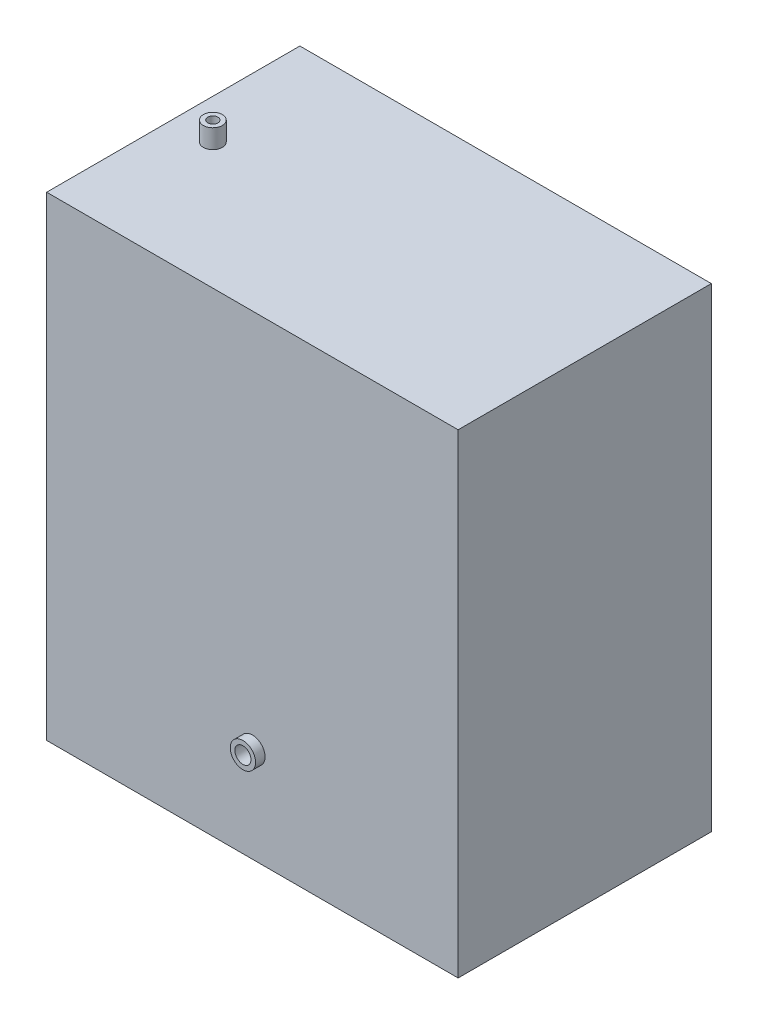
SolidWorks part; units mm, degrees
ref_plane "Front Plane" through (0, 0, 0) normal (0, 0, 1) x (1, 0, 0)
ref_plane "Top Plane" through (0, 0, 0) normal (0, 1, 0) x (1, 0, 0)
ref_plane "Right Plane" through (0, 0, 0) normal (1, 0, 0) x (0, 0, -1)
other "Configuration Table"
sketch "Sketch1" plane through (0, 0, 0) normal (0, 1, 0) x (1, 0, 0)
  line L1 (-130, -80) -> (130, -80)
  line L2 (-130, -80) -> (-130, 80)
  line L3 (-130, 80) -> (130, 80)
  line L4 (130, -80) -> (130, 80)
  line L5 (-130, -80) -> (130, 80) construction
  line L6 (-130, 80) -> (130, -80) construction
  point P6 (0, 0)
  dimension "D1" = 260
  dimension "D2" = 160
extrude "Tank_Body" add sketch "Sketch1" along normal blind 300
sketch "Sketch2" plane through (0, 0, 0) normal (0, 1, 0) x (1, 0, 0)
  line L0 (-127, -77) -> (127, -77)
  line L1 (127, -77) -> (127, 77)
  line L2 (127, 77) -> (-127, 77)
  line L3 (-127, 77) -> (-127, -77)
extrude "Inside" cut sketch "Sketch2" against normal blind 294 from offset 297
sketch "Sketch3" plane through (0, 0, 0) normal (0, 1, 0) x (1, 0, 0)
  circle A0 centre (-105, 0) radius 6
  dimension "D1" = 12
extrude "Inlet_Port" add sketch "Sketch3" along normal blind 12 from offset 300
sketch "Sketch4" plane through (0, 0, 0) normal (0, 1, 0) x (1, 0, 0)
  circle A0 centre (-105, 0) radius 3.2
  dimension "D1" = 6.4
extrude "Inlet_Socket" cut sketch "Sketch4" against normal blind 10 from offset 312
sketch "Sketch5" plane through (0, 0, 0) normal (0, 1, 0) x (1, 0, 0)
  circle A0 centre (-105, 0) radius 2
  dimension "D1" = 4
extrude "Inlet_Hole" cut sketch "Sketch5" against normal blind 5 from offset 300
sketch "Sketch6" plane through (0, 0, 0) normal (0, 0, 1) x (1, 0, 0)
  circle A0 centre (0, 60) radius 8
  dimension "D1" = 16
extrude "Outlet_Boss" add sketch "Sketch6" along normal blind 6 from offset 80
sketch "Sketch7" plane through (0, 0, 0) normal (0, 0, 1) x (1, 0, 0)
  circle A0 centre (0, 60) radius 5.1
  dimension "D1" = 10.2
extrude "Tap_Socket" cut sketch "Sketch7" against normal blind 10 from offset 86
equation "\"Jar_OD\"= 90  'ASSUMED - Part G fallback - jar outer diameter"
equation "\"Jar_H\"= 120  'ASSUMED - Part G fallback - jar height"
equation "\"Pump_L\"= 45  'ASSUMED - Part G fallback"
equation "\"Pump_W\"= 24  'ASSUMED - Part G fallback"
equation "\"Pump_H\"= 33  'ASSUMED - Part G fallback"
equation "\"Pump_Outlet_OD\"= 7.5  'ASSUMED - Part G fallback"
equation "\"Tube_OD\"= 8  'ASSUMED - Part G fallback"
equation "\"Tube_ID\"= 6  'ASSUMED - Part G fallback"
equation "\"TDS_Body_Dia\"= 12  'ASSUMED - Part G fallback"
equation "\"TDS_Wet_Len\"= 45  'ASSUMED - Part G fallback - length in water"
equation "\"DS_Tube_Dia\"= 6  'ASSUMED - Part G fallback"
equation "\"DS_Tube_Len\"= 50  'ASSUMED - Part G fallback"
equation "\"ORP_Body_Dia\"= 12  'ASSUMED - Part G fallback"
equation "\"ORP_Body_Len\"= 150  'ASSUMED - Part G fallback"
equation "\"ORP_Cap_Dia\"= 16  'ASSUMED - Part G fallback"
equation "\"Turb_W\"= 33  'ASSUMED - Part G fallback - head width"
equation "\"Turb_D\"= 28  'ASSUMED - Part G fallback - head depth"
equation "\"Turb_H\"= 30  'ASSUMED - Part G fallback - head height"
equation "\"Turb_Slot_W\"= 10  'ASSUMED - Part G fallback - slot width"
equation "\"Flow_L\"= 62  'ASSUMED - Part G fallback YF-S201"
equation "\"Flow_W\"= 36  'ASSUMED - Part G fallback"
equation "\"Flow_H\"= 35  'ASSUMED - Part G fallback"
equation "\"Thread_G12_OD\"= 20.955  'ASSUMED - Part G fallback thread G1/2 (major diameter)"
equation "\"Valve_L\"= 75  'ASSUMED - Part G fallback"
equation "\"Valve_W\"= 45  'ASSUMED - Part G fallback"
equation "\"Valve_H\"= 60  'ASSUMED - Part G fallback"
equation "\"Tee_L\"= 40  'ASSUMED - Part G fallback - overall length"
equation "\"Tee_Branch_L\"= 25  'ASSUMED - Part G fallback"
equation "\"Tee_OD\"= 12  'ASSUMED - Part G fallback"
equation "\"LED_Board_L\"= 20  'ASSUMED - Part G fallback"
equation "\"LED_Board_W\"= 20  'ASSUMED - Part G fallback - LED at centre"
equation "\"GUVA_L\"= 20  'ASSUMED - Part G fallback"
equation "\"GUVA_W\"= 12  'ASSUMED - Part G fallback - sensor at centre"
equation "\"Reed_L\"= 27  'ASSUMED - Part G fallback MC-38 half"
equation "\"Reed_W\"= 14  'ASSUMED - Part G fallback"
equation "\"Reed_H\"= 8  'ASSUMED - Part G fallback"
equation "\"ESP_L\"= 51  'ASSUMED - Part G fallback"
equation "\"ESP_W\"= 28  'ASSUMED - Part G fallback"
equation "\"TFT_L\"= 58  'ASSUMED - Part G fallback - board"
equation "\"TFT_W\"= 35  'ASSUMED - Part G fallback - board"
equation "\"TFT_Win_L\"= 35  'ASSUMED - Part G fallback - visible window"
equation "\"TFT_Win_W\"= 28  'ASSUMED - Part G fallback - visible window"
equation "\"Relay_L\"= 50  'ASSUMED - Part G fallback"
equation "\"Relay_W\"= 26  'ASSUMED - Part G fallback"
equation "\"Relay_H\"= 19  'ASSUMED - Part G fallback"
equation "\"Mosfet_L\"= 34  'ASSUMED - Part G fallback"
equation "\"Mosfet_W\"= 17  'ASSUMED - Part G fallback"
equation "\"Mosfet_H\"= 12  'ASSUMED - Part G fallback"
equation "\"TDS_Board_L\"= 42  'ASSUMED - Part G fallback"
equation "\"TDS_Board_W\"= 32  'ASSUMED - Part G fallback"
equation "\"Turb_Board_L\"= 38  'ASSUMED - Part G fallback"
equation "\"Turb_Board_W\"= 28  'ASSUMED - Part G fallback"
equation "\"BNC_Thread_Dia\"= 9.5  'ASSUMED - Part G fallback"
equation "\"Plate_L\"= 420  'ASSUMED - Part G fallback"
equation "\"Plate_W\"= 297  'ASSUMED - Part G fallback"
equation "\"Plate_T\"= 6  'ASSUMED - Part G fallback"
equation "\"Booster_L\"= 150  'ASSUMED - Part G fallback - booster pump"
equation "\"Booster_W\"= 95  'ASSUMED - Part G fallback"
equation "\"Booster_H\"= 100  'ASSUMED - Part G fallback"
equation "\"PTube_OD\"= 6.35  'ASSUMED - Part G fallback - product tube 1/4 inch"
equation "\"Qz_Out\"= 12  'ASSUMED - Part G fallback - quartz channel outside square"
equation "\"Qz_Path\"= 10  'ASSUMED - Part G fallback - quartz channel inside light path"
equation "\"Qz_L\"= 40  'ASSUMED - Part G fallback - quartz channel length"
equation "\"LED860_Dia\"= 5  'ASSUMED - Part G fallback - 860 nm LED"
equation "\"BPW_L\"= 5.4  'ASSUMED - Part G fallback - BPW34"
equation "\"BPW_W\"= 4.3  'ASSUMED - Part G fallback - BPW34"
equation "\"Cart_Dia\"= 50  'ASSUMED - Part G fallback - sediment and pre-carbon cartridges"
equation "\"Cart_L\"= 255  'ASSUMED - Part G fallback"
equation "\"UF_Dia\"= 50  'ASSUMED - Part G fallback - UF cartridge"
equation "\"UF_L\"= 260  'ASSUMED - Part G fallback"
equation "\"RO_Dia\"= 62  'ASSUMED - Part G fallback - RO membrane housing"
equation "\"RO_L\"= 300  'ASSUMED - Part G fallback"
equation "\"UVC_Dia\"= 40  'ASSUMED - Part G fallback - UV-C chamber"
equation "\"UVC_L\"= 300  'ASSUMED - Part G fallback"
equation "\"Tank_W\"= 260  'ASSUMED - Part G fallback - storage tank"
equation "\"Tank_D\"= 160  'ASSUMED - Part G fallback"
equation "\"Tank_H\"= 300  'ASSUMED - Part G fallback"
equation "\"Cab_W\"= 400  'ASSUMED - Part G fallback - purifier cabinet"
equation "\"Cab_D\"= 270  'ASSUMED - Part G fallback"
equation "\"Cab_H\"= 560  'ASSUMED - Part G fallback"
equation "\"ORP_Board_L\"= 40  'ASSUMED - Part G fallback - ORP buffer board"
equation "\"ORP_Board_W\"= 30  'ASSUMED - Part G fallback"
equation "\"Opt_Board_L\"= 50  'ASSUMED - Part G fallback - optical front-end board"
equation "\"Opt_Board_W\"= 40  'ASSUMED - Part G fallback"
equation "\"Buck_L\"= 43  'ASSUMED - Part G fallback - 12 V to 5 V buck module"
equation "\"Buck_W\"= 21  'ASSUMED - Part G fallback"
equation "\"Buck_H\"= 14  'ASSUMED - Part G fallback"
equation "\"BB_L\"= 165  'ASSUMED - Part G fallback - breadboard (As_Built_R3 only)"
equation "\"BB_W\"= 55  'ASSUMED - Part G fallback"
equation "\"BB_H\"= 10  'ASSUMED - Part G fallback"
equation "\"Cuv_W\"= 12.5  'ASSUMED - old R3 cuvette (station suppressed in SS4)"
equation "\"Cuv_D\"= 12.5  'ASSUMED - old R3 cuvette (station suppressed in SS4)"
equation "\"Cuv_H\"= 45  'ASSUMED - old R3 cuvette (station suppressed in SS4)"
equation "\"Probe_Clr\"= 0.3  'DESIGN VALUE - Part C rule 3 - printed probe hole = diameter + 0.3"
equation "\"Label_H\"= 0.6  'DESIGN VALUE - Part D - raised label height"
equation "\"D1@Sketch1\" = \"Tank_W\""
equation "\"D2@Sketch1\" = \"Tank_D\""
equation "\"D1@Tank_Body\" = \"Tank_H\""
